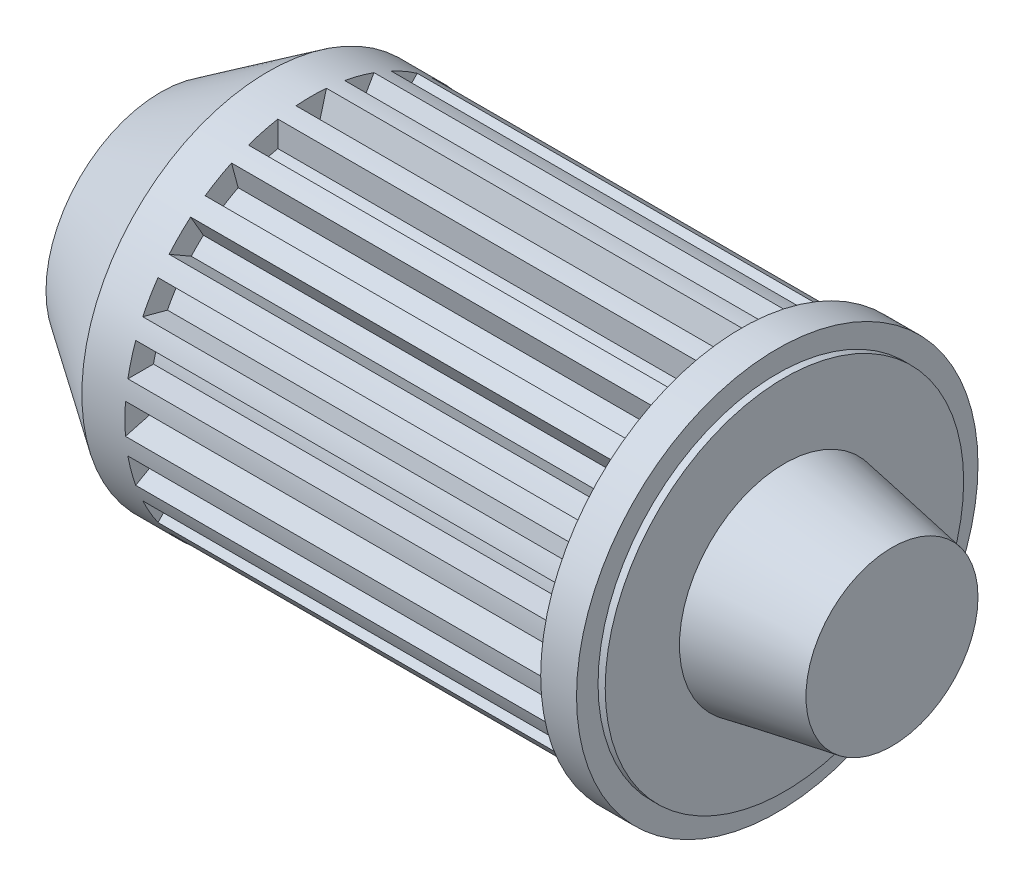
SolidWorks part; units mm, degrees
ref_plane "Front Plane" through (0, 0, 0) normal (0, 0, 1) x (1, 0, 0)
ref_plane "Top Plane" through (0, 0, 0) normal (0, 1, 0) x (1, 0, 0)
ref_plane "Right Plane" through (0, 0, 0) normal (1, 0, 0) x (0, 0, -1)
sketch "Sketch1" plane through (0, 0, 0) normal (1, 0, 0) x (0, 0, -1)
  circle A0 centre (0, 0) radius 280
  dimension "D1" = 560
extrude "Boss-Extrude1" add sketch "Sketch1" along normal blind 50
sketch "Sketch2" plane through (50, 0, 0) normal (1, 0, 0) x (0, 0, -1)
  circle A0 centre (0, 0) radius 250
  dimension "D1" = 500
extrude "Boss-Extrude2" add sketch "Sketch2" along normal blind 10
sketch "Sketch3" plane through (60, 0, 0) normal (1, 0, 0) x (0, 0, -1)
  circle A0 centre (0, 0) radius 120
extrude "Boss-Extrude3" add sketch "Sketch3" along normal blind 150
draft "Draft1" type of draft neutral plane draft angle 10 faces to draft 1 face at (210, 0, -120) neutral plane through (210, 0, 0) neutral plane normal (1, 0, 0) parameters "D1"=10
sketch "Sketch4" plane through (0, 0, 0) normal (-1, 0, 0) x (0, 0, 1)
  circle A0 centre (0, 0) radius 260
extrude "Boss-Extrude4" add sketch "Sketch4" along normal blind 600
sketch "Sketch5" plane through (-600, 0, 0) normal (-1, 0, 0) x (0, 0, 1)
  line L0 (87.5502, 244.8162) -> (46.5874, 173.8666)
  line L1 (21.2039, 259.1339) -> (0, 180)
  line L2 (-21.2039, 259.1339) -> (0, 180)
  line L3 (46.5874, 255.7921) -> (46.5874, 173.8666)
  line L4 (147.9301, 213.8146) -> (90, 155.8846)
  line L5 (111.2039, 235.0185) -> (90, 155.8846)
  line L6 (198.2288, 168.242) -> (127.2792, 127.2792)
  line L7 (168.242, 198.2288) -> (127.2792, 127.2792)
  line L8 (235.0185, 111.2039) -> (155.8846, 90)
  line L9 (213.8146, 147.9301) -> (155.8846, 90)
  line L10 (255.7921, 46.5874) -> (173.8666, 46.5874)
  line L11 (244.8162, 87.5502) -> (173.8666, 46.5874)
  line L12 (259.1339, -21.2039) -> (180, 0)
  line L13 (259.1339, 21.2039) -> (180, 0)
  line L14 (244.8162, -87.5502) -> (173.8666, -46.5874)
  line L15 (255.7921, -46.5874) -> (173.8666, -46.5874)
  line L16 (213.8146, -147.9301) -> (155.8846, -90)
  line L17 (235.0185, -111.2039) -> (155.8846, -90)
  line L18 (168.242, -198.2288) -> (127.2792, -127.2792)
  line L19 (198.2288, -168.242) -> (127.2792, -127.2792)
  line L20 (111.2039, -235.0185) -> (90, -155.8846)
  line L21 (147.9301, -213.8146) -> (90, -155.8846)
  line L22 (46.5874, -255.7921) -> (46.5874, -173.8666)
  line L23 (87.5502, -244.8162) -> (46.5874, -173.8666)
  line L24 (-21.2039, -259.1339) -> (0, -180)
  line L25 (21.2039, -259.1339) -> (0, -180)
  line L26 (-87.5502, -244.8162) -> (-46.5874, -173.8666)
  line L27 (-46.5874, -255.7921) -> (-46.5874, -173.8666)
  line L28 (-147.9301, -213.8146) -> (-90, -155.8846)
  line L29 (-111.2039, -235.0185) -> (-90, -155.8846)
  line L30 (-198.2288, -168.242) -> (-127.2792, -127.2792)
  line L31 (-168.242, -198.2288) -> (-127.2792, -127.2792)
  line L32 (-235.0185, -111.2039) -> (-155.8846, -90)
  line L33 (-213.8146, -147.9301) -> (-155.8846, -90)
  line L34 (-255.7921, -46.5874) -> (-173.8666, -46.5874)
  line L35 (-244.8162, -87.5502) -> (-173.8666, -46.5874)
  line L36 (-259.1339, 21.2039) -> (-180, 0)
  line L37 (-259.1339, -21.2039) -> (-180, 0)
  line L38 (-244.8162, 87.5502) -> (-173.8666, 46.5874)
  line L39 (-255.7921, 46.5874) -> (-173.8666, 46.5874)
  line L40 (-213.8146, 147.9301) -> (-155.8846, 90)
  line L41 (-235.0185, 111.2039) -> (-155.8846, 90)
  line L42 (-168.242, 198.2288) -> (-127.2792, 127.2792)
  line L43 (-198.2288, 168.242) -> (-127.2792, 127.2792)
  line L44 (-111.2039, 235.0185) -> (-90, 155.8846)
  line L45 (-147.9301, 213.8146) -> (-90, 155.8846)
  line L46 (-46.5874, 255.7921) -> (-46.5874, 173.8666)
  line L47 (-87.5502, 244.8162) -> (-46.5874, 173.8666)
  arc A0 (21.2039, 259.1339) -> (-21.2039, 259.1339) centre (0, 0) ccw
  arc A1 (87.5502, 244.8162) -> (46.5874, 255.7921) centre (0, 0) ccw
  arc A2 (147.9301, 213.8146) -> (111.2039, 235.0185) centre (0, 0) ccw
  arc A3 (198.2288, 168.242) -> (168.242, 198.2288) centre (0, 0) ccw
  arc A4 (235.0185, 111.2039) -> (213.8146, 147.9301) centre (0, 0) ccw
  arc A5 (255.7921, 46.5874) -> (244.8162, 87.5502) centre (0, 0) ccw
  arc A6 (259.1339, -21.2039) -> (259.1339, 21.2039) centre (0, 0) ccw
  arc A7 (244.8162, -87.5502) -> (255.7921, -46.5874) centre (0, 0) ccw
  arc A8 (213.8146, -147.9301) -> (235.0185, -111.2039) centre (0, 0) ccw
  arc A9 (168.242, -198.2288) -> (198.2288, -168.242) centre (0, 0) ccw
  arc A10 (111.2039, -235.0185) -> (147.9301, -213.8146) centre (0, 0) ccw
  arc A11 (46.5874, -255.7921) -> (87.5502, -244.8162) centre (0, 0) ccw
  arc A12 (-21.2039, -259.1339) -> (21.2039, -259.1339) centre (0, 0) ccw
  arc A13 (-87.5502, -244.8162) -> (-46.5874, -255.7921) centre (0, 0) ccw
  arc A14 (-147.9301, -213.8146) -> (-111.2039, -235.0185) centre (0, 0) ccw
  arc A15 (-198.2288, -168.242) -> (-168.242, -198.2288) centre (0, 0) ccw
  arc A16 (-235.0185, -111.2039) -> (-213.8146, -147.9301) centre (0, 0) ccw
  arc A17 (-255.7921, -46.5874) -> (-244.8162, -87.5502) centre (0, 0) ccw
  arc A18 (-259.1339, 21.2039) -> (-259.1339, -21.2039) centre (0, 0) ccw
  arc A19 (-244.8162, 87.5502) -> (-255.7921, 46.5874) centre (0, 0) ccw
  arc A20 (-213.8146, 147.9301) -> (-235.0185, 111.2039) centre (0, 0) ccw
  arc A21 (-168.242, 198.2288) -> (-198.2288, 168.242) centre (0, 0) ccw
  arc A22 (-111.2039, 235.0185) -> (-147.9301, 213.8146) centre (0, 0) ccw
  arc A23 (-46.5874, 255.7921) -> (-87.5502, 244.8162) centre (0, 0) ccw
  point P77 (0, 0)
  dimension "D1" = 24
extrude "Cut-Extrude1" cut sketch "Sketch5" against normal blind 600
sketch "Sketch6" plane through (-600, 0, 0) normal (-1, 0, 0) x (0, 0, 1)
  circle A0 centre (0, 0) radius 225
  dimension "D1" = 450
extrude "Boss-Extrude5" add sketch "Sketch6" against normal blind 600
sketch "Sketch7" plane through (-600, 0, 0) normal (-1, 0, 0) x (0, 0, 1)
  circle A0 centre (0, 0) radius 260
extrude "Boss-Extrude6" add sketch "Sketch7" along normal blind 60
sketch "Sketch8" plane through (-660, 0, 0) normal (-1, 0, 0) x (0, 0, 1)
  circle A0 centre (0, 0) radius 260
ref_plane "Plane1" through (-810, 0, 0) normal (-1, 0, 0) x (0, 0, 1)
sketch "Sketch9" plane through (-810, 0, 0) normal (-1, 0, 0) x (0, 0, 1)
  circle A0 centre (0, 0) radius 160
loft "Loft1" add profiles "Sketch9" section face at (-660, 0, 260) section "Sketch9"
